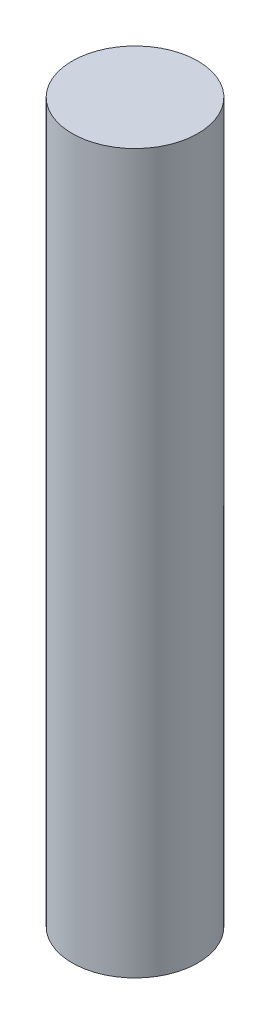
SolidWorks part; units mm, degrees
material "Commercially Pure CP-Ti UNS R50400 (SS)"
ref_plane "Front Plane" through (0, 0, 0) normal (0, 0, 1) x (1, 0, 0)
ref_plane "Top Plane" through (0, 0, 0) normal (0, 1, 0) x (1, 0, 0)
ref_plane "Right Plane" through (0, 0, 0) normal (1, 0, 0) x (0, 0, -1)
sketch "Sketch1" plane through (0, 0, 0) normal (0, 1, 0) x (1, 0, 0)
  circle A0 centre (0, 0) radius 2.667
  dimension "D1" = 5.334
extrude "Boss-Extrude1" add sketch "Sketch1" along normal blind 30.48
